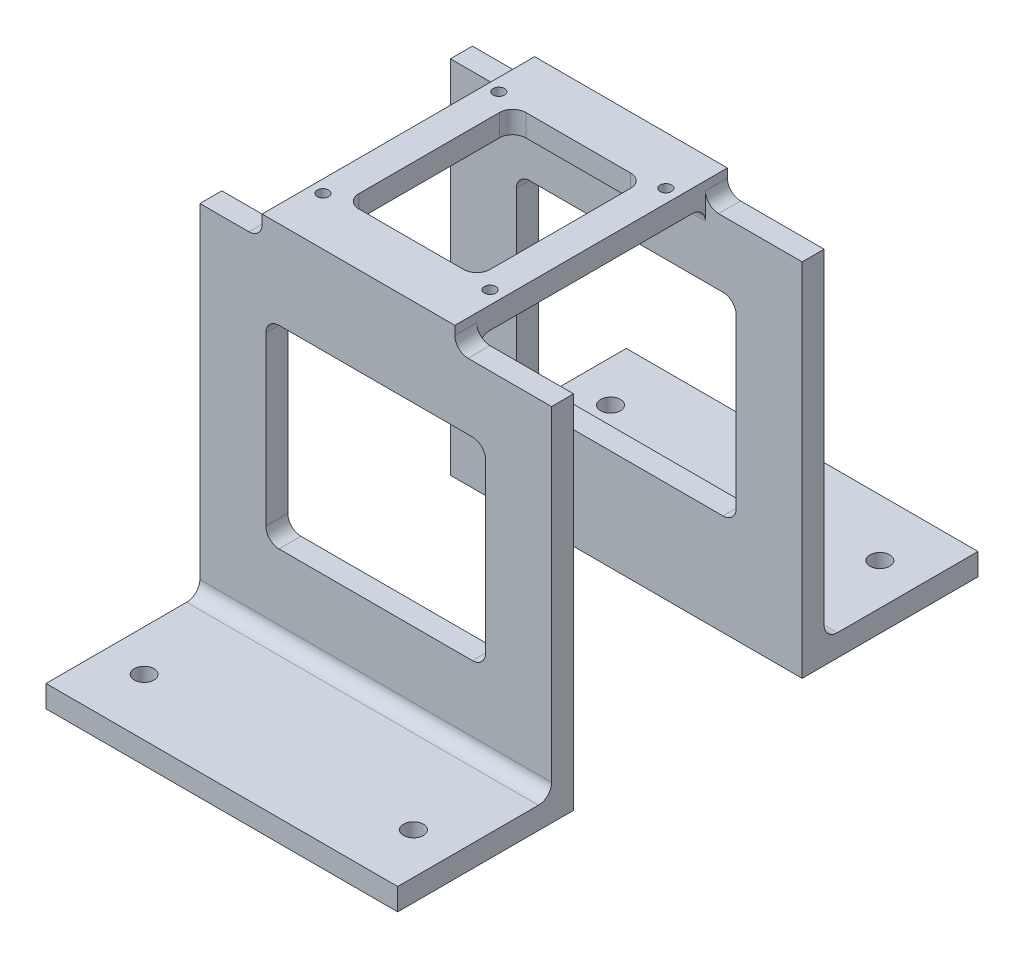
SolidWorks part; units mm, degrees
ref_plane "Front Plane" through (0, 0, 0) normal (0, 0, 1) x (1, 0, 0)
ref_plane "Top Plane" through (0, 0, 0) normal (0, 1, 0) x (1, 0, 0)
ref_plane "Right Plane" through (0, 0, 0) normal (1, 0, 0) x (0, 0, -1)
sketch "Sketch1" plane through (0, 0, 0) normal (0, 1, 0) x (1, 0, 0)
  line L0 (0, 0) -> (0, 66) construction
  line L1 (-40, 66) -> (40, 66)
  line L2 (-40, 66) -> (-40, 26)
  line L3 (-40, 26) -> (40, 26)
  line L4 (40, 66) -> (40, 26)
  line L5 (0, 0) -> (-30.625, 53.0441) construction
  line L6 (-55, 0) -> (55, 0) construction
  line L7 (40, -66) -> (40, -26)
  line L8 (-40, -26) -> (40, -26)
  line L9 (-40, -66) -> (-40, -26)
  line L10 (-40, -66) -> (40, -66)
  circle A0 centre (-30.625, 53.0441) radius 2.25
  circle A1 centre (30.625, 53.0441) radius 2.25
  circle A2 centre (30.625, -53.0441) radius 2.25
  circle A3 centre (-30.625, -53.0441) radius 2.25
  dimension "D7" = 4.5
  dimension "D1" = 26
  dimension "D2" = 40
  dimension "D3" = 80
  dimension "D4" = 40
  dimension "D5" = 61.25
  dimension "D6" = 30
extrude "Boss-Extrude1" add sketch "Sketch1" along normal blind 5
sketch "Sketch2" plane through (0, 5, 0) normal (0, 1, 0) x (1, 0, 0)
  line L0 (40, 26) -> (40, 66) construction
  line L1 (-40, 26) -> (40, 26)
  line L2 (-40, 26) -> (-40, 31)
  line L3 (-40, 31) -> (40, 31)
  line L4 (40, 26) -> (40, 31)
  line L5 (-55, 0) -> (55, 0) construction
  line L6 (40, -26) -> (40, -31)
  line L7 (-40, -31) -> (40, -31)
  line L8 (-40, -26) -> (-40, -31)
  line L9 (-40, -26) -> (40, -26)
  dimension "D1" = 5
extrude "Boss-Extrude2" add sketch "Sketch2" along normal blind 77.05
sketch "Sketch3" plane through (0, 82.05, 0) normal (0, 1, 0) x (1, 0, 0)
  line L1 (-25.85, 31) -> (18, 31)
  line L2 (-25.85, 31) -> (-25.85, -31)
  line L3 (-25.85, -31) -> (18, -31)
  line L4 (18, 31) -> (18, -31)
  line L5 (40, -66) -> (40, -31) construction
  line L7 (-40, -31) -> (40, -31) construction
  dimension "D1" = 62
  dimension "D2" = 43.85
  dimension "D3" = 22
  dimension "D4" = 0
extrude "Boss-Extrude3" add sketch "Sketch3" along normal blind 5 contours L2 L3 L4 L1
sketch "Sketch5" plane through (0, 82.05, 0) normal (0, -1, 0) x (1, 0, 0)
  line L0 (-25.85, -26) -> (-25.85, 26) construction
  line L1 (-18.85, 19) -> (11, 19)
  line L2 (-18.85, 19) -> (-18.85, -19)
  line L3 (-18.85, -19) -> (11, -19)
  line L4 (11, 19) -> (11, -19)
  line L5 (-40, 26) -> (40, 26) construction
  line L6 (18, -26) -> (18, 26) construction
  line L7 (-40, -26) -> (40, -26) construction
  dimension "D1" = 7
  dimension "D2" = 7
  dimension "D3" = 7
  dimension "D4" = 7
extrude "Cut-Extrude2" cut sketch "Sketch5" against normal blind 10
sketch "Sketch4" plane through (0, 87.05, 0) normal (0, 1, 0) x (1, 0, 0)
  line L1 (-23, 20) -> (15, 20) construction
  line L2 (-23, 20) -> (-23, -20) construction
  line L3 (-23, -20) -> (15, -20) construction
  line L4 (15, 20) -> (15, -20) construction
  circle A0 centre (-23, 20) radius 1.3
  circle A1 centre (15, 20) radius 1.3
  circle A2 centre (15, -20) radius 1.3
  circle A3 centre (-23, -20) radius 1.3
  dimension "D5" = 2.6
  dimension "D1" = 23
  dimension "D2" = 40
  dimension "D3" = 38
  dimension "D4" = 20
extrude "Cut-Extrude1" cut sketch "Sketch4" against normal up to next
fillet "Fillet1" radius 3 4 edges at (-3.925, 82.05, -26) (-3.925, 82.05, 26) (0, 5, -31) (0, 5, 31)
fillet "Fillet2" radius 3 4 edges at (18, 82.05, -28.5) (-25.85, 82.05, -28.5) (-25.85, 82.05, 28.5) (18, 82.05, 28.5)
sketch "Sketch6" plane through (0, 0, 31) normal (0, 0, 1) x (1, 0, 0)
  line L0 (-40, 82.05) -> (-40, 8) construction
  line L1 (-25, 67.05) -> (25, 67.05)
  line L2 (-25, 67.05) -> (-25, 23)
  line L3 (-25, 23) -> (25, 23)
  line L4 (25, 67.05) -> (25, 23)
  line L5 (-40, 8) -> (40, 8) construction
  line L6 (40, 82.05) -> (40, 8) construction
  line L7 (21, 82.05) -> (40, 82.05) construction
  dimension "D1" = 15
  dimension "D2" = 15
  dimension "D3" = 15
  dimension "D4" = 15
extrude "Cut-Extrude3" cut sketch "Sketch6" along normal through all both and the other way through all
fillet "Fillet3" radius 3 12 edges at (-25, 67.05, -28.5) (25, 67.05, -28.5) (25, 23, -28.5) (-25, 23, -28.5) (-25, 67.05, 28.5) (25, 67.05, 28.5) (25, 23, 28.5) (-25, 23, 28.5) (-18.85, 84.55, -19) (-18.85, 84.55, 19) (11, 84.55, 19) (11, 84.55, -19)
